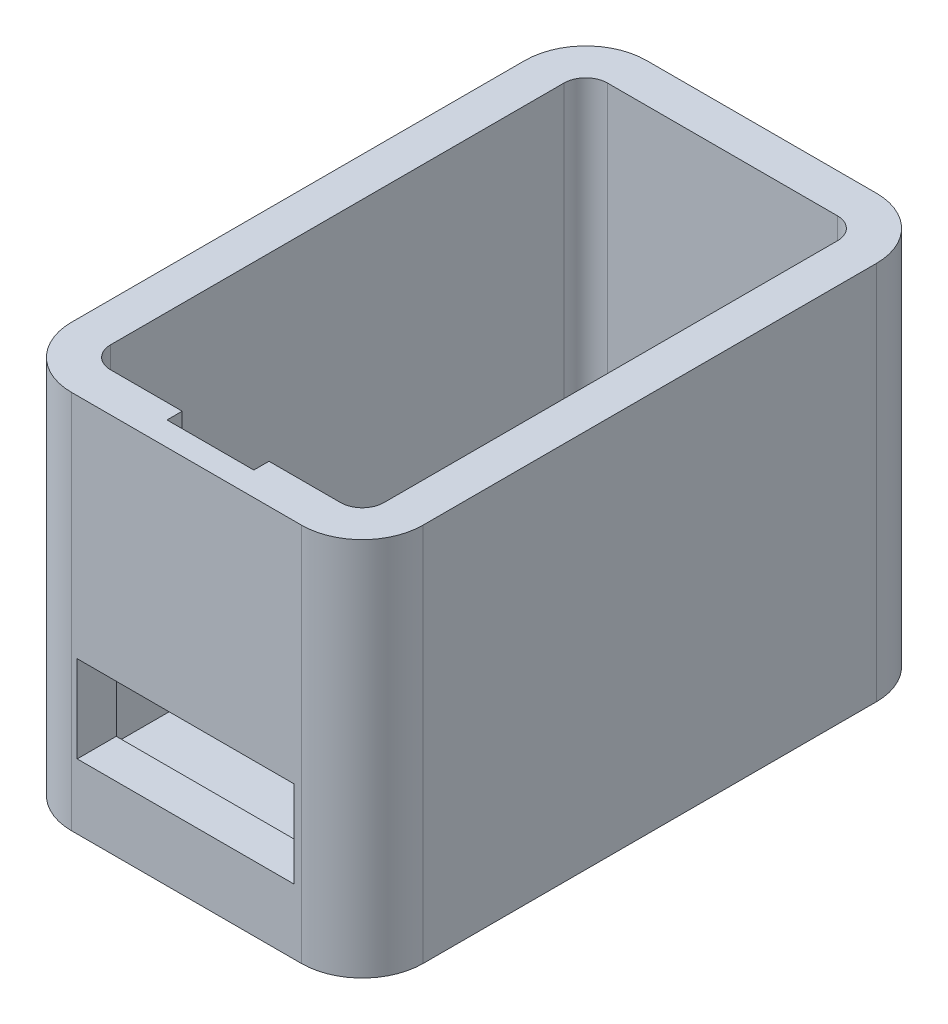
SolidWorks part; units mm, degrees
ref_plane "Front Plane" through (0, 0, 0) normal (0, 0, 1) x (1, 0, 0)
ref_plane "Top Plane" through (0, 0, 0) normal (0, 1, 0) x (1, 0, 0)
ref_plane "Right Plane" through (0, 0, 0) normal (1, 0, 0) x (0, 0, -1)
sketch "Sketch1" plane through (0, 0, 0) normal (0, 1, 0) x (1, 0, 0)
  line L0 (-5.25, 13.3) -> (5.35, 13.3)
  line L1 (-5.25, 11.5) -> (5.35, 11.5)
  line L2 (-6.25, 10.5) -> (-6.25, -10.4)
  line L3 (-5.25, -11.4) -> (5.35, -11.4)
  line L4 (6.35, 10.5) -> (6.35, -10.4)
  line L5 (8.15, 10.5) -> (8.15, -10.4)
  line L6 (-5.25, -13.2) -> (5.35, -13.2)
  line L7 (-8.05, 10.5) -> (-8.05, -10.4)
  arc A0 (-6.25, -10.4) -> (-5.25, -11.4) centre (-5.25, -10.4) ccw
  arc A1 (5.35, -11.4) -> (6.35, -10.4) centre (5.35, -10.4) ccw
  arc A2 (5.35, 11.5) -> (6.35, 10.5) centre (5.35, 10.5) cw
  arc A3 (-5.25, 11.5) -> (-6.25, 10.5) centre (-5.25, 10.5) ccw
  arc A4 (5.35, 13.3) -> (8.15, 10.5) centre (5.35, 10.5) cw
  arc A5 (5.35, -13.2) -> (8.15, -10.4) centre (5.35, -10.4) ccw
  arc A6 (-8.05, -10.4) -> (-5.25, -13.2) centre (-5.25, -10.4) ccw
  arc A7 (-5.25, 13.3) -> (-8.05, 10.5) centre (-5.25, 10.5) ccw
  point P0 (0, 0)
  dimension "D3" = 1
  dimension "D1" = 12.6
  dimension "D2" = 22.9
  dimension "D4" = 1.8
extrude "Boss-Extrude1" add sketch "Sketch1" along normal blind 16
sketch "Sketch2" plane through (0, 0, 0) normal (0, -1, 0) x (1, 0, 0)
  line L0 (-5.25, 13.2) -> (5.35, 13.2) construction
  line L1 (-8.05, -10.5) -> (-8.05, 10.4) construction
  line L2 (8.15, 10.4) -> (8.15, -10.5) construction
  line L3 (5.35, -13.3) -> (-5.25, -13.3) construction
  line L4 (-5.25, 13.2) -> (5.35, 13.2)
  line L5 (-8.05, -10.5) -> (-8.05, 10.4)
  line L6 (8.15, 10.4) -> (8.15, -10.5)
  line L7 (5.35, -13.3) -> (-5.25, -13.3)
  arc A0 (8.15, 10.4) -> (5.35, 13.2) centre (5.35, 10.4) ccw construction
  arc A1 (-5.25, 13.2) -> (-8.05, 10.4) centre (-5.25, 10.4) ccw construction
  arc A2 (5.35, -13.3) -> (8.15, -10.5) centre (5.35, -10.5) ccw construction
  arc A3 (-8.05, -10.5) -> (-5.25, -13.3) centre (-5.25, -10.5) ccw construction
  arc A4 (8.15, 10.4) -> (5.35, 13.2) centre (5.35, 10.4) ccw
  arc A5 (-5.25, 13.2) -> (-8.05, 10.4) centre (-5.25, 10.4) ccw
  arc A6 (5.35, -13.3) -> (8.15, -10.5) centre (5.35, -10.5) ccw
  arc A7 (-8.05, -10.5) -> (-5.25, -13.3) centre (-5.25, -10.5) ccw
extrude "Boss-Extrude2" add sketch "Sketch2" along normal blind 1.5
sketch "Sketch3" plane through (0, 0, 13.2) normal (0, 0, 1) x (1, 0, 0)
  line L0 (0, 0) -> (0.05, 16) construction
  line L1 (-5.25, 16) -> (5.35, 16) construction
  line L3 (-3.4549, 5.5) -> (3.4285, 5.5) construction
  line L4 (-3.4549, 1.5) -> (3.4354, 1.5) construction
  line L10 (-4.9891, 5.5) -> (5.0109, 5.5)
  line L11 (-4.9891, 5.5) -> (-4.9891, 1.5)
  line L12 (-4.9891, 1.5) -> (5.0109, 1.5)
  line L13 (5.0109, 5.5) -> (5.0109, 1.5)
  line L14 (-4.9891, 5.5) -> (5.0109, 1.5) construction
  line L15 (-4.9891, 1.5) -> (5.0109, 5.5) construction
  point P11 (0.0109, 3.5)
  dimension "D1" = 1.5
  dimension "D2" = 4
  dimension "D3" = 10
extrude "Cut-Extrude1" cut sketch "Sketch3" against normal blind 2.5
sketch "Sketch5" plane through (0, 16, 0) normal (0, 1, 0) x (1, 0, 0)
  line L0 (-5.25, -11.4) -> (5.35, -11.4) construction
  line L1 (-1.95, -10.7) -> (2.05, -10.7)
  line L2 (-1.95, -10.7) -> (-1.95, -12.1)
  line L3 (-1.95, -12.1) -> (2.05, -12.1)
  line L4 (2.05, -10.7) -> (2.05, -12.1)
  line L5 (-1.95, -10.7) -> (2.05, -12.1) construction
  line L6 (-1.95, -12.1) -> (2.05, -10.7) construction
  point P0 (0.05, -11.4)
  dimension "D1" = 1.4
  dimension "D2" = 4.2379
  dimension "D3" = 4
extrude "Cut-Extrude2" cut sketch "Sketch5" against normal blind 14
